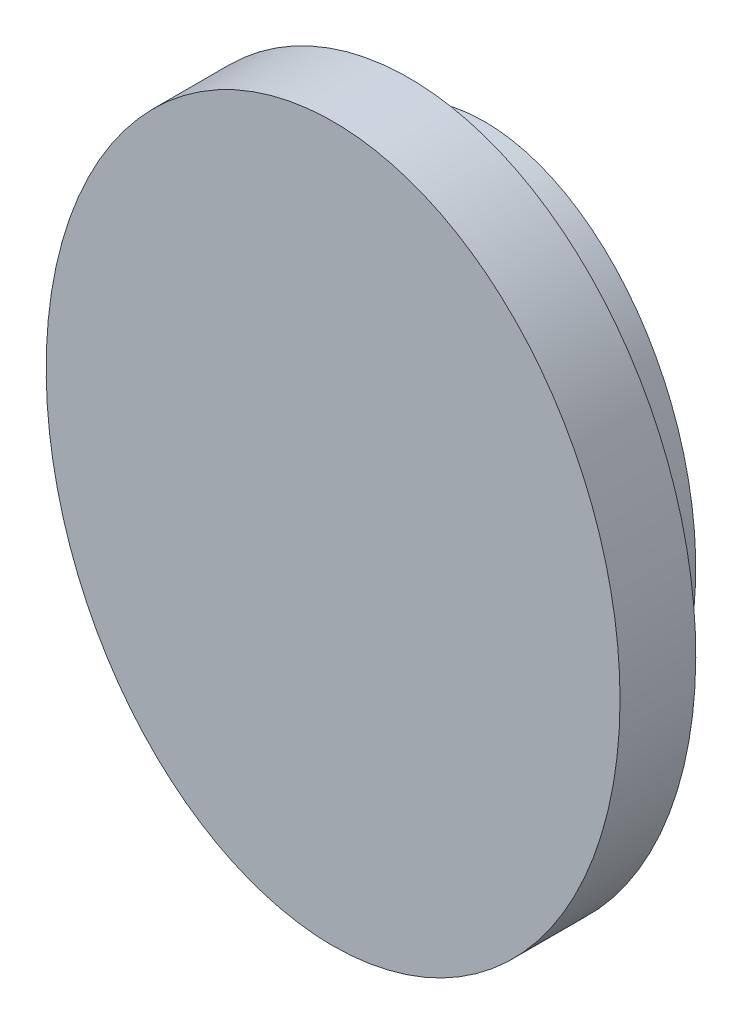
SolidWorks part; units mm, degrees
material "1023 Carbon Steel Sheet (SS)"
ref_plane "Front Plane" through (0, 0, 0) normal (0, 0, 1) x (1, 0, 0)
ref_plane "Top Plane" through (0, 0, 0) normal (0, 1, 0) x (1, 0, 0)
ref_plane "Right Plane" through (0, 0, 0) normal (1, 0, 0) x (0, 0, -1)
sketch "Sketch2" plane through (0, 0, 0) normal (0, 0, 1) x (1, 0, 0)
  spline S2 degree 3 poles (1.27, 19.495) (0.7202, 19.495) (0.1858, 19.4089) (-0.5948, 19.1622) (-0.8506, 19.06) (-1.3407, 18.8248) (-1.5769, 18.6911) (-2.0332, 18.3942) (-2.2544, 18.23) (-2.6724, 17.8813) (-2.8701, 17.6965) (-3.2457, 17.3079) (-3.4235, 17.1042) (-3.7604, 16.6793) (-3.9202, 16.4571) (-4.368, 15.7726) (-4.6231, 15.2964) (-5.0589, 14.3103) (-5.2396, 13.8003) (-5.6754, 12.2218) (-5.8151, 11.1505) (-5.8154, 9.518) (-5.7794, 8.9746) (-5.6374, 7.9066) (-5.5315, 7.3792) (-5.317, 6.5988) (-5.2362, 6.3405) (-5.0548, 5.8276) (-4.9541, 5.573) (-4.6256, 4.8281) (-4.3705, 4.3522) (-3.9272, 3.673) (-3.7692, 3.4525) (-3.4307, 3.0243) (-3.2509, 2.8178) (-2.6857, 2.2321) (-2.2725, 1.8826) (-1.5852, 1.4338) (-1.3469, 1.2986) (-0.8583, 1.0633) (-0.6068, 0.9624) (-0.0885, 0.7971) (0.1806, 0.7327) (0.7177, 0.6474) (0.9871, 0.6257) (1.5279, 0.6244) (1.8001, 0.6449) (2.3426, 0.729) (2.6074, 0.7916) (3.3841, 1.0358) (3.8831, 1.2775) (4.5672, 1.7215) (4.7858, 1.8834) (5.2054, 2.2324) (5.4066, 2.4201) (5.9735, 3.006) (6.3077, 3.4307) (6.9022, 4.3377) (7.1627, 4.8227) (7.6, 5.8123) (7.7796, 6.3206) (7.9956, 7.1017) (8.0586, 7.3651) (8.1669, 7.8982) (8.2121, 8.1682) (8.3197, 8.9758) (8.3551, 9.515) (8.3555, 10.595) (8.3206, 11.1362) (8.1769, 12.2183) (8.0697, 12.7481) (7.7842, 13.7851) (7.6059, 14.2922) (7.1707, 15.2815) (6.9108, 15.7674) (6.3176, 16.6759) (5.9838, 17.1018) (5.4169, 17.69) (5.2158, 17.8783) (4.7977, 18.2274) (4.5801, 18.3893) (4.1262, 18.6855) (3.8899, 18.8199) (3.3963, 19.0577) (3.1413, 19.1597) (2.6237, 19.3241) (2.3598, 19.3873) (1.8209, 19.4729) (1.5449, 19.495) (1.27, 19.495) (0.7202, 19.495) (0.1858, 19.4089) knots -0.015625 0 0 0 0.03125 0.03125 0.046875 0.046875 0.0625 0.0625 0.078125 0.078125 0.09375 0.09375 0.109375 0.109375 0.125 0.125 0.15625 0.15625 0.1875 0.1875 0.25 0.25 0.28125 0.28125 0.3125 0.3125 0.328125 0.328125 0.34375 0.34375 0.375 0.375 0.390625 0.390625 0.40625 0.40625 0.4375 0.4375 0.453125 0.453125 0.46875 0.46875 0.484375 0.484375 0.5 0.5 0.515625 0.515625 0.53125 0.53125 0.5625 0.5625 0.578125 0.578125 0.59375 0.59375 0.625 0.625 0.65625 0.65625 0.6875 0.6875 0.703125 0.703125 0.71875 0.71875 0.75 0.75 0.78125 0.78125 0.8125 0.8125 0.84375 0.84375 0.875 0.875 0.90625 0.90625 0.921875 0.921875 0.9375 0.9375 0.953125 0.953125 0.96875 0.96875 0.984375 0.984375 1 1 1 1.03125 1.03125 1.046875 only from (1.27, 19.495) to (1.27, 19.495)
  spline S3 degree 3 poles (1.27, 19.495) (0.7202, 19.495) (0.1858, 19.4089) (-0.5948, 19.1622) (-0.8506, 19.06) (-1.3407, 18.8248) (-1.5769, 18.6911) (-2.0332, 18.3942) (-2.2544, 18.23) (-2.6724, 17.8813) (-2.8701, 17.6965) (-3.2457, 17.3079) (-3.4235, 17.1042) (-3.7604, 16.6793) (-3.9202, 16.4571) (-4.368, 15.7726) (-4.6231, 15.2964) (-5.0589, 14.3103) (-5.2396, 13.8003) (-5.6754, 12.2218) (-5.8151, 11.1505) (-5.8154, 9.518) (-5.7794, 8.9746) (-5.6374, 7.9066) (-5.5315, 7.3792) (-5.317, 6.5988) (-5.2362, 6.3405) (-5.0548, 5.8276) (-4.9541, 5.573) (-4.6256, 4.8281) (-4.3705, 4.3522) (-3.9272, 3.673) (-3.7692, 3.4525) (-3.4307, 3.0243) (-3.2509, 2.8178) (-2.6857, 2.2321) (-2.2725, 1.8826) (-1.5852, 1.4338) (-1.3469, 1.2986) (-0.8583, 1.0633) (-0.6068, 0.9624) (-0.0885, 0.7971) (0.1806, 0.7327) (0.7177, 0.6474) (0.9871, 0.6257) (1.5279, 0.6244) (1.8001, 0.6449) (2.3426, 0.729) (2.6074, 0.7916) (3.3841, 1.0358) (3.8831, 1.2775) (4.5672, 1.7215) (4.7858, 1.8834) (5.2054, 2.2324) (5.4066, 2.4201) (5.9735, 3.006) (6.3077, 3.4307) (6.9022, 4.3377) (7.1627, 4.8227) (7.6, 5.8123) (7.7796, 6.3206) (7.9956, 7.1017) (8.0586, 7.3651) (8.1669, 7.8982) (8.2121, 8.1682) (8.3197, 8.9758) (8.3551, 9.515) (8.3555, 10.595) (8.3206, 11.1362) (8.1769, 12.2183) (8.0697, 12.7481) (7.7842, 13.7851) (7.6059, 14.2922) (7.1707, 15.2815) (6.9108, 15.7674) (6.3176, 16.6759) (5.9838, 17.1018) (5.4169, 17.69) (5.2158, 17.8783) (4.7977, 18.2274) (4.5801, 18.3893) (4.1262, 18.6855) (3.8899, 18.8199) (3.3963, 19.0577) (3.1413, 19.1597) (2.6237, 19.3241) (2.3598, 19.3873) (1.8209, 19.4729) (1.5449, 19.495) (1.27, 19.495) (0.7202, 19.495) (0.1858, 19.4089) knots -0.015625 0 0 0 0.03125 0.03125 0.046875 0.046875 0.0625 0.0625 0.078125 0.078125 0.09375 0.09375 0.109375 0.109375 0.125 0.125 0.15625 0.15625 0.1875 0.1875 0.25 0.25 0.28125 0.28125 0.3125 0.3125 0.328125 0.328125 0.34375 0.34375 0.375 0.375 0.390625 0.390625 0.40625 0.40625 0.4375 0.4375 0.453125 0.453125 0.46875 0.46875 0.484375 0.484375 0.5 0.5 0.515625 0.515625 0.53125 0.53125 0.5625 0.5625 0.578125 0.578125 0.59375 0.59375 0.625 0.625 0.65625 0.65625 0.6875 0.6875 0.703125 0.703125 0.71875 0.71875 0.75 0.75 0.78125 0.78125 0.8125 0.8125 0.84375 0.84375 0.875 0.875 0.90625 0.90625 0.921875 0.921875 0.9375 0.9375 0.953125 0.953125 0.96875 0.96875 0.984375 0.984375 1 1 1 1.03125 1.03125 1.046875 only from (1.27, 19.495) to (1.27, 19.495)
  dimension "D1" = 0
extrude "Boss-Extrude1" add sketch "Sketch2" against normal blind 2.54
sketch "Sketch3" plane through (0, 0, 0) normal (0, 0, 1) x (1, 0, 0)
  ellipse E2 centre (1.27, 10.06) end of major axis (1.27, -1.915) minor radius 9.6253
  ellipse E3 centre (1.27, 10.06) end of major axis (1.27, -1.915) minor radius 9.6253
  dimension "D1" = 0
extrude "Boss-Extrude2" add sketch "Sketch3" along normal blind 2.54
